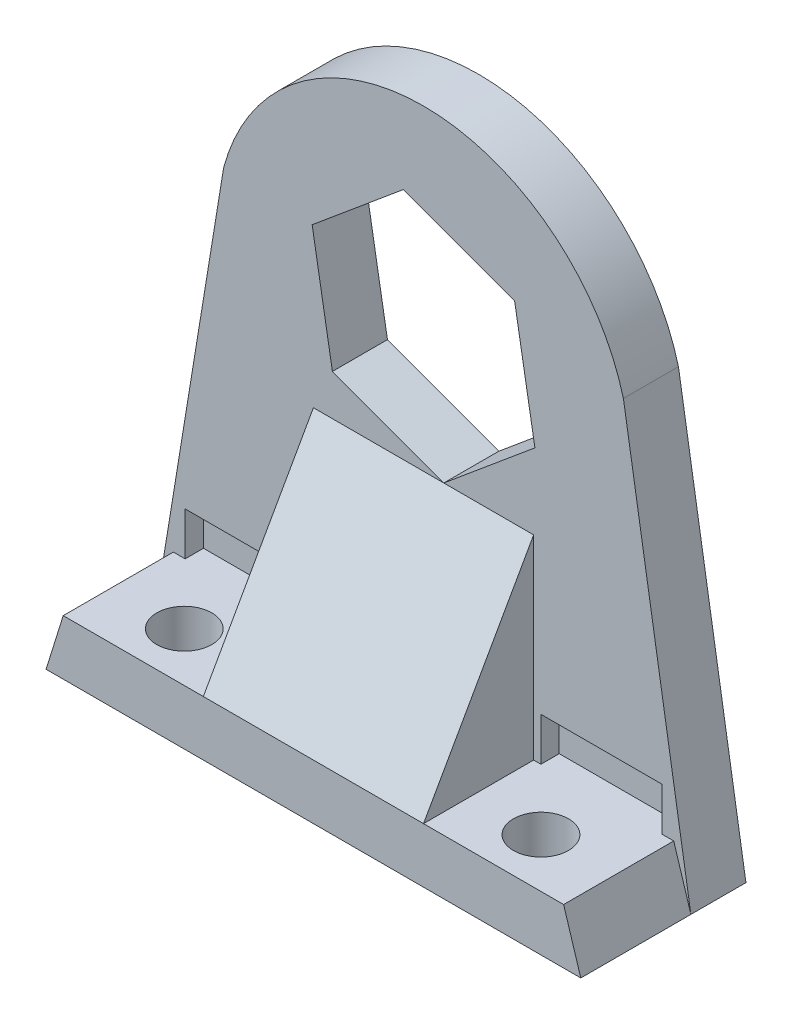
SolidWorks part; units mm, degrees
material "ABS"
ref_plane "前视基准面" through (0, 0, 0) normal (0, 0, 1) x (1, 0, 0)
ref_plane "上视基准面" through (0, 0, 0) normal (0, 1, 0) x (1, 0, 0)
ref_plane "右视基准面" through (0, 0, 0) normal (1, 0, 0) x (0, 0, -1)
sketch "草图1" plane through (0, 0, 0) normal (0, 0, 1) x (1, 0, 0)
  line L0 (0, 0) -> (0, -11.15) construction
  line L1 (0, -11.15) -> (-14.5697, -11.15)
  line L2 (-10.1102, 3.1524) -> (-14.5697, -11.15)
  line L3 (10.1102, 3.1524) -> (14.5697, -11.15)
  line L4 (0, -11.15) -> (14.5697, -11.15)
  line L5 (14.5697, -11.15) -> (14.9782, -11.5105)
  circle A0 centre (0, 0) radius 6.5
  arc A1 (10.1102, 3.1524) -> (-10.1102, 3.1524) centre (0, 0) ccw
  dimension "D1" = 13
  dimension "D2" = 11.15
extrude "凸台-拉伸1" add sketch "草图1" along normal blind 3
sketch "草图4" plane through (0, 0, 3) normal (0, 0, 1) x (1, 0, 0)
  line L0 (0, -11.15) -> (0, -8.15) construction
  line L1 (-14.5697, -11.15) -> (14.5697, -11.15) construction
  line L2 (0, -8.15) -> (13.6343, -8.15)
  line L3 (10.1102, 3.1524) -> (14.5697, -11.15) construction
  line L4 (13.6343, -8.15) -> (14.5697, -11.15)
  line L5 (14.5697, -11.15) -> (-14.5697, -11.15)
  line L6 (-14.5697, -11.15) -> (-13.6343, -8.15)
  line L7 (-10.1102, 3.1524) -> (-14.5697, -11.15) construction
  line L8 (-13.6343, -8.15) -> (0, -8.15)
  dimension "D1" = 3
extrude "凸台-拉伸2" add sketch "草图4" along normal blind 6
sketch "草图5" plane through (0, -8.15, 0) normal (0, 1, 0) x (1, 0, 0)
  line L0 (0, 1.9221) -> (0, -11.8551) construction
  circle A0 centre (-9.7186, -6.3193) radius 1.5
  circle A1 centre (9.7186, -6.3193) radius 1.5
  dimension "D1" = 3
extrude "切除-拉伸1" cut sketch "草图5" against normal blind 6
sketch "草图6" plane through (0, 0, 0) normal (0, 0, -1) x (-1, 0, 0)
  line L0 (0, -11.5591) -> (0, 8.4409) construction
  line L1 (14.5697, -11.15) -> (10.8926, 11.3631)
  line L2 (-14.5697, -11.15) -> (14.5697, -11.15)
  line L3 (-14.5697, -11.15) -> (-10.8926, 11.3631)
  arc A0 (11.2563, 9.1363) -> (-11.2563, 9.1363) centre (0, 8.4409) ccw
  dimension "D1" = 20
extrude "凸台-拉伸3" add sketch "草图6" against normal blind 3
sketch "草图7" plane through (0, 0, 0) normal (0, 0, -1) x (-1, 0, 0)
  circle A0 centre (0, 0) radius 7.582
extrude "凸台-拉伸4" add sketch "草图7" against normal blind 3
sketch "草图8" plane through (0, 0, 0) normal (0, 0, -1) x (-1, 0, 0)
  line L0 (0, -11.15) -> (0, 8.85) construction
  line L1 (14.5697, -11.15) -> (-14.5697, -11.15) construction
  line L3 (1.1035, 15.2215) -> (-4.9661, 12.9914)
  line L4 (-4.9661, 12.9914) -> (-6.0696, 6.6199)
  line L5 (-6.0696, 6.6199) -> (-1.1035, 2.4785)
  line L6 (-1.1035, 2.4785) -> (4.9661, 4.7086)
  line L7 (4.9661, 4.7086) -> (6.0696, 11.0801)
  line L8 (6.0696, 11.0801) -> (1.1035, 15.2215)
  circle A0 centre (0, 8.85) radius 5.6 construction
  dimension "D2" = 11.2
  dimension "D1" = 20
extrude "切除-拉伸2" cut sketch "草图8" against normal blind 3
sketch "草图9" plane through (0, 0, 0) normal (1, 0, 0) x (0, 0, -1)
  line L0 (-9, -8.15) -> (-3, 2.4785)
  line L1 (-3, 2.4785) -> (-3, -8.15)
  line L2 (-3, -8.15) -> (-9, -8.15)
extrude "凸台-拉伸5" add sketch "草图9" along normal mid plane 12
sketch "草图10" plane through (0, 0, 3) normal (0, 0, 1) x (1, 0, 0)
  line L0 (-6, -8.15) -> (-13.6343, -8.15) construction
  line L1 (-12.9915, -8.15) -> (-6.3952, -8.15)
  line L2 (-12.9915, -8.15) -> (-12.9915, -5.7911)
  line L3 (-12.9915, -5.7911) -> (-6.3952, -5.7911)
  line L4 (-6.3952, -8.15) -> (-6.3952, -5.7911)
  line L5 (0, -0.5624) -> (0, -10.0144) construction
  line L6 (6.3952, -8.15) -> (6.3952, -5.7911)
  line L7 (12.9915, -5.7911) -> (6.3952, -5.7911)
  line L8 (12.9915, -8.15) -> (12.9915, -5.7911)
  line L9 (12.9915, -8.15) -> (6.3952, -8.15)
extrude "切除-拉伸3" cut sketch "草图10" against normal blind 1
